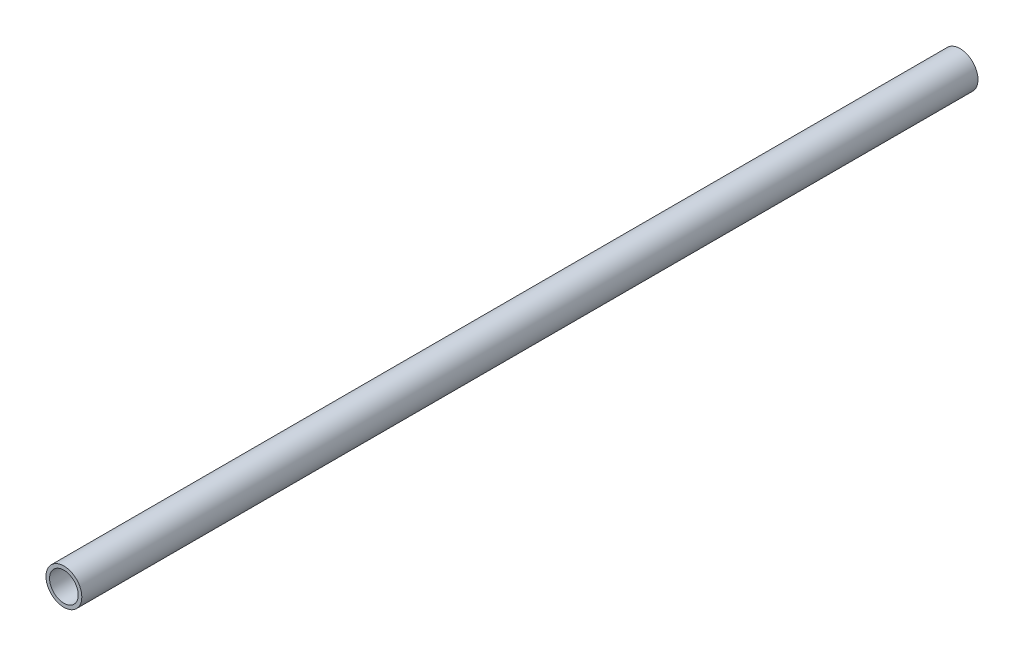
SolidWorks part; units mm, degrees
material "EM-CF"
ref_plane "Płaszczyzna przednia" through (0, 0, 0) normal (0, 0, 1) x (1, 0, 0)
ref_plane "Płaszczyzna górna" through (0, 0, 0) normal (0, 1, 0) x (1, 0, 0)
ref_plane "Płaszczyzna prawa" through (0, 0, 0) normal (1, 0, 0) x (0, 0, -1)
sketch "Szkic1" plane through (0, 0, 0) normal (0, 0, 1) x (1, 0, 0)
  circle A0 centre (0, 0) radius 4
  circle A1 centre (0, 0) radius 5
  dimension "D1" = 1
  dimension "D2" = 10
extrude "Dodanie-wyciągnięcie1" add sketch "Szkic1" along normal blind 250
